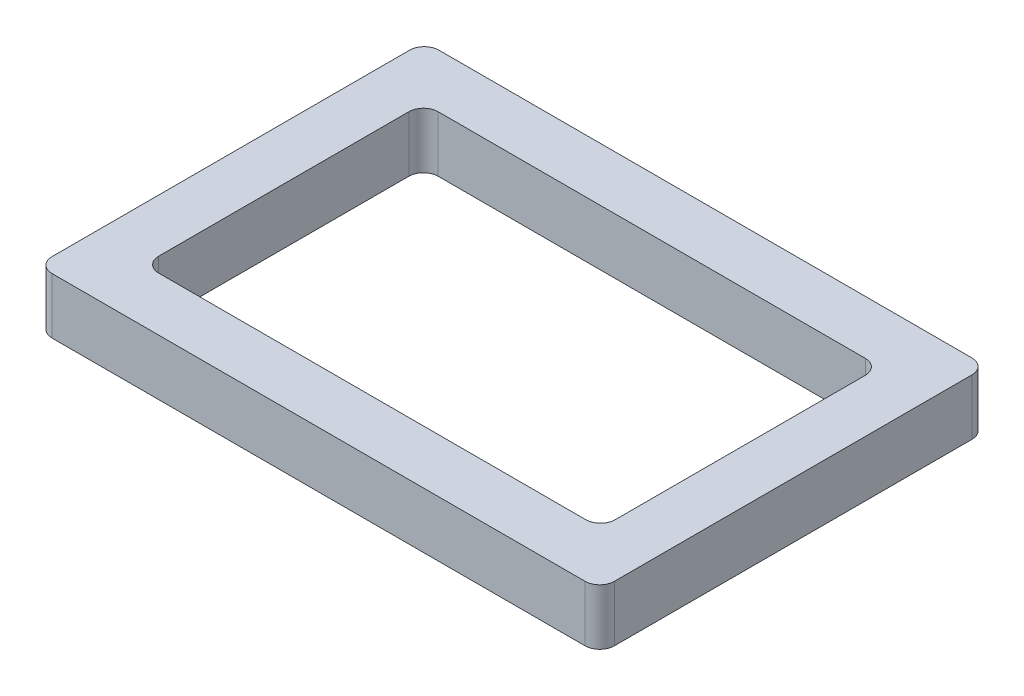
SolidWorks part; units mm, degrees
ref_plane "Front Plane" through (0, 0, 0) normal (0, 0, 1) x (1, 0, 0)
ref_plane "Top Plane" through (0, 0, 0) normal (0, 1, 0) x (1, 0, 0)
ref_plane "Right Plane" through (0, 0, 0) normal (1, 0, 0) x (0, 0, -1)
sketch "Sketch1" plane through (0, 0, 0) normal (0, 1, 0) x (1, 0, 0)
  line L1 (-181.65, -131.85) -> (181.65, -131.85)
  line L2 (-191.65, -121.85) -> (-191.65, 121.85)
  line L3 (-181.65, 131.85) -> (181.65, 131.85)
  line L4 (191.65, -121.85) -> (191.65, 121.85)
  line L5 (-191.65, -131.85) -> (191.65, 131.85) construction
  line L6 (-191.65, 131.85) -> (191.65, -131.85) construction
  line L7 (-145.575, -95.25) -> (145.575, -95.25)
  line L8 (-155.575, -85.25) -> (-155.575, 85.25)
  line L9 (-145.575, 95.25) -> (145.575, 95.25)
  line L10 (155.575, -85.25) -> (155.575, 85.25)
  line L11 (-155.575, -95.25) -> (155.575, 95.25) construction
  line L12 (-155.575, 95.25) -> (155.575, -95.25) construction
  arc A0 (-191.65, 121.85) -> (-181.65, 131.85) centre (-181.65, 121.85) cw
  arc A1 (191.65, 121.85) -> (181.65, 131.85) centre (181.65, 121.85) ccw
  arc A2 (181.65, -131.85) -> (191.65, -121.85) centre (181.65, -121.85) ccw
  arc A3 (-191.65, -121.85) -> (-181.65, -131.85) centre (-181.65, -121.85) ccw
  arc A4 (-145.575, 95.25) -> (-155.575, 85.25) centre (-145.575, 85.25) ccw
  arc A5 (155.575, 85.25) -> (145.575, 95.25) centre (145.575, 85.25) ccw
  arc A6 (145.575, -95.25) -> (155.575, -85.25) centre (145.575, -85.25) ccw
  arc A7 (-155.575, -85.25) -> (-145.575, -95.25) centre (-145.575, -85.25) ccw
  point P0 (0, 0)
  point P18 (0, 0)
  dimension "D3" = 10
  dimension "D4" = 10
  dimension "D5" = 10
  dimension "D6" = 10
  dimension "D9" = 10
  dimension "D10" = 10
  dimension "D11" = 10
  dimension "D12" = 10
  dimension "D1" = 383.3
  dimension "D2" = 263.7
  dimension "D7" = 190.5
  dimension "D8" = 311.15
  dimension "D13" = 36.6
  dimension "D14" = 36.075
extrude "Boss-Extrude1" add sketch "Sketch1" along normal blind 38.1
